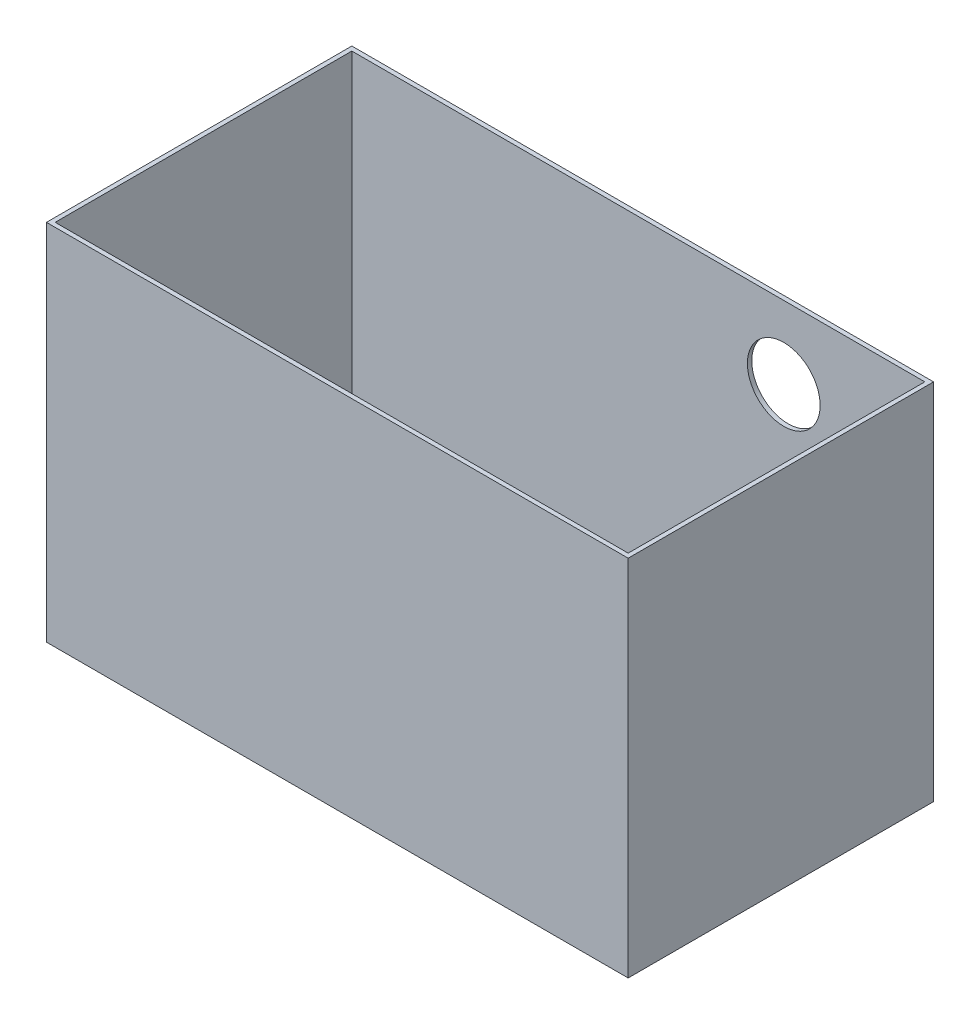
SolidWorks part; units mm, degrees
ref_plane "Front Plane" through (0, 0, 0) normal (0, 0, 1) x (1, 0, 0)
ref_plane "Top Plane" through (0, 0, 0) normal (0, 1, 0) x (1, 0, 0)
ref_plane "Right Plane" through (0, 0, 0) normal (1, 0, 0) x (0, 0, -1)
sketch "Sketch1" plane through (0, 0, 0) normal (0, 1, 0) x (1, 0, 0)
  line L1 (0, 0) -> (400, 0)
  line L2 (0, 0) -> (0, -210)
  line L3 (0, -210) -> (400, -210)
  line L4 (400, 0) -> (400, -210)
  dimension "D1" = 400
  dimension "D2" = 210
extrude "Extrude-Thin1" add sketch "Sketch1" along normal blind 250 thin
sketch "Sketch4" plane through (0, 0, 0) normal (0, 0, -1) x (-1, 0, 0)
  line L0 (-400, 250) -> (0, 250) construction
  line L1 (-400, 250) -> (-400, 0) construction
  circle A0 centre (-300, 200) radius 25
  dimension "D2" = 50
  dimension "D3" = 100
  dimension "D1" = 50
extrude "Cut-Extrude1" cut sketch "Sketch4" against normal blind 10
